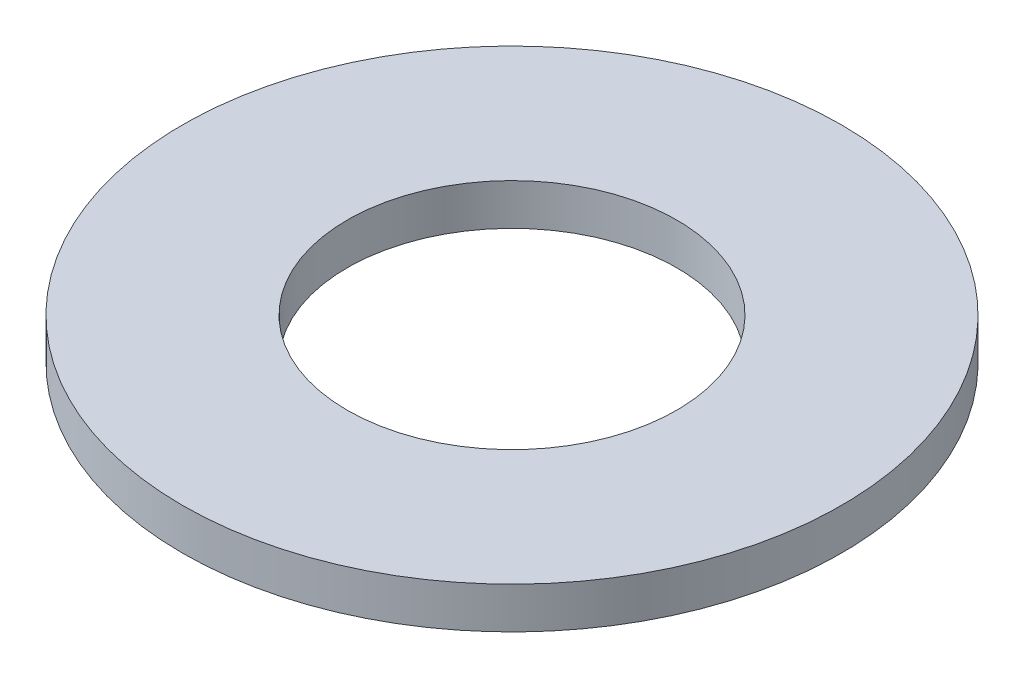
SolidWorks part; units mm, degrees
ref_plane "Front Plane" through (0, 0, 0) normal (0, 0, 1) x (1, 0, 0)
ref_plane "Top Plane" through (0, 0, 0) normal (0, 1, 0) x (1, 0, 0)
ref_plane "Right Plane" through (0, 0, 0) normal (1, 0, 0) x (0, 0, -1)
sketch "Sketch1" plane through (0, 0, 0) normal (0, 1, 0) x (1, 0, 0)
  circle A0 centre (0, 0) radius 10.3187
  circle A1 centre (0, 0) radius 5.1594
  dimension "D1" = 20.6375
  dimension "D2" = 10.3187
extrude "Boss-Extrude1" add sketch "Sketch1" along normal blind 1.2954
